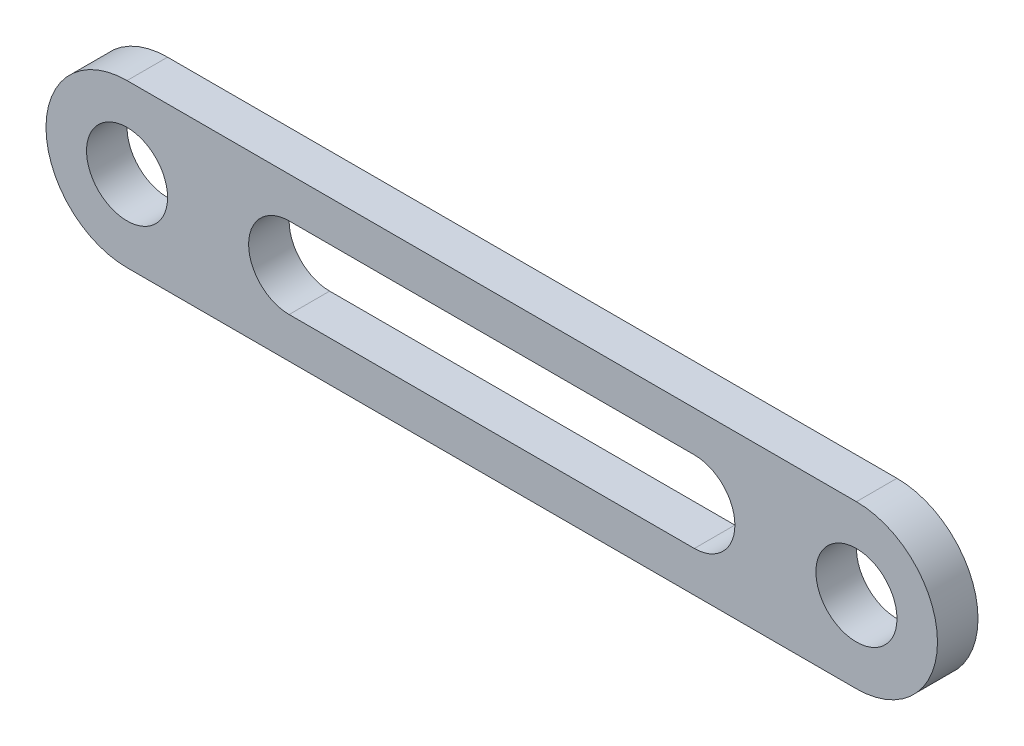
SolidWorks part; units mm, degrees
ref_plane "Plano frontal" through (0, 0, 0) normal (0, 0, 1) x (1, 0, 0)
ref_plane "Plano superior" through (0, 0, 0) normal (0, 1, 0) x (1, 0, 0)
ref_plane "Plano direito" through (0, 0, 0) normal (1, 0, 0) x (0, 0, -1)
sketch "Esboço1" plane through (0, 0, 0) normal (0, 0, 1) x (1, 0, 0)
  line L1 (-70, 5) -> (-20, 5)
  line L3 (-70, -5) -> (-20, -5)
  line L9 (-90, 10) -> (0, 10)
  line L10 (-90, 5) -> (-90, -5)
  line L11 (-90, -10) -> (0, -10)
  line L12 (0, 5) -> (0, -5)
  arc A0 (0, -10) -> (0, 10) centre (0, 0) ccw
  arc A1 (-90, 10) -> (-90, -10) centre (-90, 0) ccw
  circle A2 centre (-90, 0) radius 5
  circle A3 centre (0, 0) radius 5
  arc A4 (-70, 5) -> (-70, -5) centre (-70, 0) ccw
  arc A5 (-20, -5) -> (-20, 5) centre (-20, 0) ccw
  dimension "D1" = 20
  dimension "D2" = 90
  dimension "D3" = 10
  dimension "D8" = 10
  dimension "D4" = 20
  dimension "D5" = 20
  dimension "D6" = 10
  dimension "D7" = 10
extrude "Ressalto-extrusão1" add sketch "Esboço1" along normal blind 5 contours L9 A1 L11 A0 A5 L3 A4 L1 A3 A2
